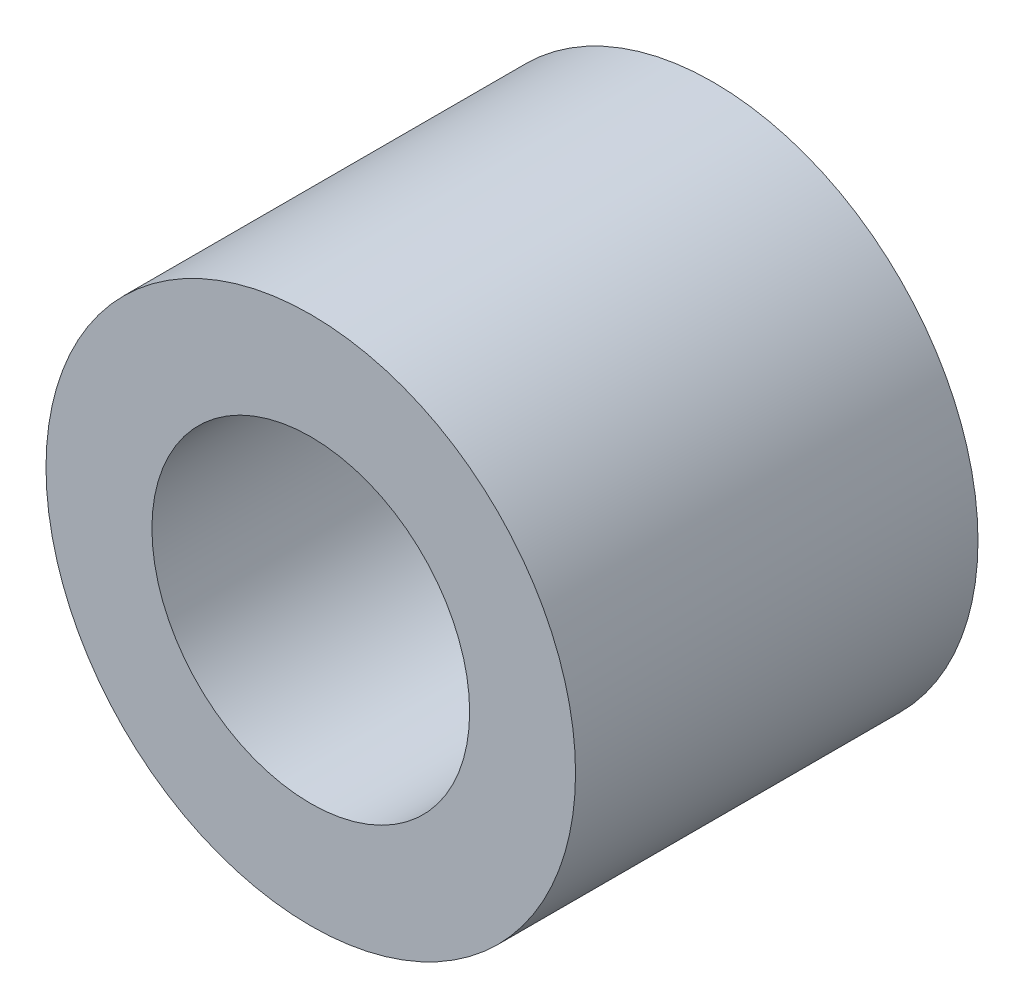
SolidWorks part; units mm, degrees
material "Brass"
ref_plane "Front Plane" through (0, 0, 0) normal (0, 0, 1) x (1, 0, 0)
ref_plane "Top Plane" through (0, 0, 0) normal (0, 1, 0) x (1, 0, 0)
ref_plane "Right Plane" through (0, 0, 0) normal (1, 0, 0) x (0, 0, -1)
sketch "Sketch1" plane through (0, 0, 0) normal (0, 0, 1) x (1, 0, 0)
  circle A0 centre (0, 0) radius 1.5
  circle A1 centre (0, 0) radius 2.5
  dimension "D1" = 3
  dimension "D2" = 5
extrude "Boss-Extrude1" add sketch "Sketch1" along normal blind 3.8
